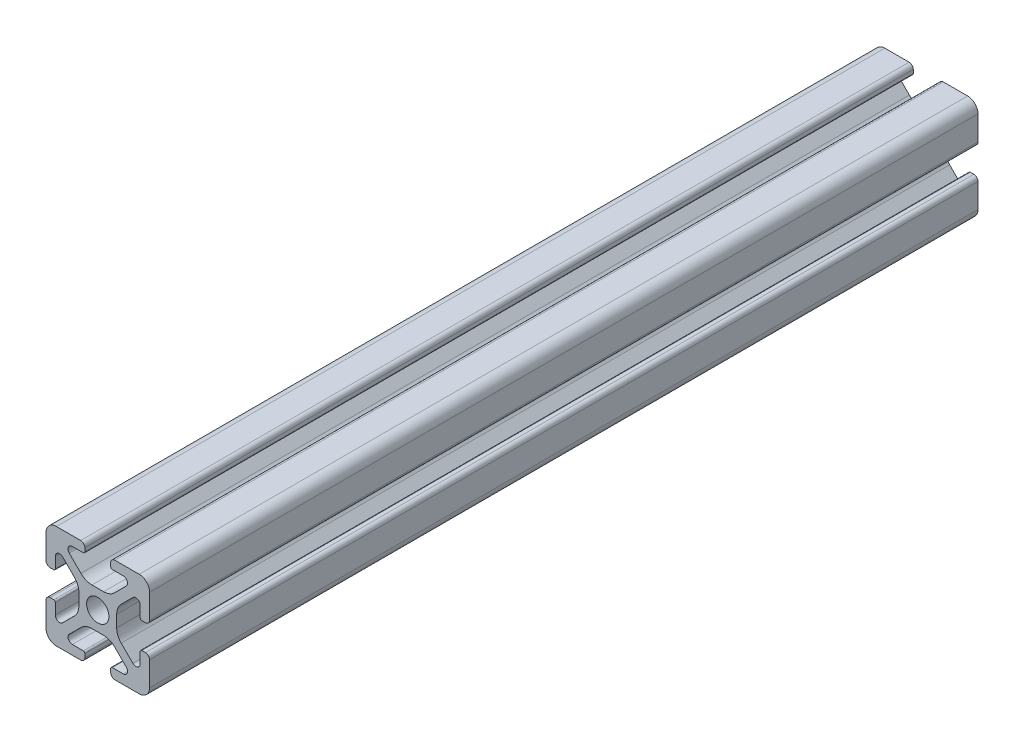
SolidWorks part; units mm, degrees
material "Alliage 1060"
ref_plane "Plan de face" through (0, 0, 0) normal (0, 0, 1) x (1, 0, 0)
ref_plane "Plan de dessus" through (0, 0, 0) normal (0, 1, 0) x (1, 0, 0)
ref_plane "Plan de droite" through (0, 0, 0) normal (1, 0, 0) x (0, 0, -1)
sketch "Esquisse1" plane through (0, 0, 0) normal (0, 0, 1) x (1, 0, 0)
  line L108 (-3.2559, 4.5287) -> (-5.5062, 6.779)
  line L109 (-4.9176, 8.2) -> (-2.8, 8.2)
  line L110 (-2.5, 8.5) -> (-2.5, 9.2)
  line L111 (-3.3, 10) -> (-8, 10)
  line L112 (-10, 8) -> (-10, 3.3)
  line L113 (-9.2, 2.5) -> (-8.5, 2.5)
  line L114 (-8.2, 2.8) -> (-8.2, 4.9176)
  line L115 (-6.779, 5.5062) -> (-4.5287, 3.2559)
  line L116 (-3.65, 1.1346) -> (-3.65, -1.1346)
  line L117 (-4.5287, -3.2559) -> (-6.779, -5.5062)
  line L118 (-8.2, -4.9176) -> (-8.2, -2.8)
  line L119 (-8.5, -2.5) -> (-9.2, -2.5)
  line L120 (-10, -3.3) -> (-10, -8)
  line L121 (-8, -10) -> (-3.3, -10)
  line L122 (-2.5, -9.2) -> (-2.5, -8.5)
  line L123 (-2.8, -8.2) -> (-4.9176, -8.2)
  line L124 (-5.5062, -6.779) -> (-3.2559, -4.5287)
  line L125 (-1.1346, -3.65) -> (1.1346, -3.65)
  line L126 (3.2559, -4.5287) -> (5.5062, -6.779)
  line L127 (4.9176, -8.2) -> (2.8, -8.2)
  line L128 (2.5, -8.5) -> (2.5, -9.2)
  line L129 (3.3, -10) -> (8, -10)
  line L130 (10, -8) -> (10, -3.3)
  line L131 (9.2, -2.5) -> (8.5, -2.5)
  line L132 (8.2, -2.8) -> (8.2, -4.9176)
  line L133 (6.779, -5.5062) -> (4.5287, -3.2559)
  line L134 (3.65, -1.1346) -> (3.65, 1.1346)
  line L135 (4.5287, 3.2559) -> (6.779, 5.5062)
  line L136 (8.2, 4.9176) -> (8.2, 2.8)
  line L137 (8.5, 2.5) -> (9.2, 2.5)
  line L138 (10, 3.3) -> (10, 8)
  line L139 (8, 10) -> (3.3, 10)
  line L140 (2.5, 9.2) -> (2.5, 8.5)
  line L141 (2.8, 8.2) -> (4.9176, 8.2)
  line L142 (5.5062, 6.779) -> (3.2559, 4.5287)
  line L143 (1.1346, 3.65) -> (-1.1346, 3.65)
  arc A42 (-2.15, 0) -> (2.15, 0) centre (0, 0) ccw
  arc A43 (2.15, 0) -> (-2.15, 0) centre (0, 0) ccw
  arc A108 (-4.9176, 8.2) -> (-5.5062, 6.779) centre (-4.9176, 7.3676) ccw
  arc A109 (-2.8, 8.2) -> (-2.5, 8.5) centre (-2.8, 8.5) ccw
  arc A110 (-2.5, 9.2) -> (-3.3, 10) centre (-3.3, 9.2) ccw
  arc A111 (-8, 10) -> (-10, 8) centre (-8, 8) ccw
  arc A112 (-10, 3.3) -> (-9.2, 2.5) centre (-9.2, 3.3) ccw
  arc A113 (-8.5, 2.5) -> (-8.2, 2.8) centre (-8.5, 2.8) ccw
  arc A114 (-6.779, 5.5062) -> (-8.2, 4.9176) centre (-7.3676, 4.9176) ccw
  arc A115 (-3.65, 1.1346) -> (-4.5287, 3.2559) centre (-6.65, 1.1346) ccw
  arc A116 (-4.5287, -3.2559) -> (-3.65, -1.1346) centre (-6.65, -1.1346) ccw
  arc A117 (-8.2, -4.9176) -> (-6.779, -5.5062) centre (-7.3676, -4.9176) ccw
  arc A118 (-8.2, -2.8) -> (-8.5, -2.5) centre (-8.5, -2.8) ccw
  arc A119 (-9.2, -2.5) -> (-10, -3.3) centre (-9.2, -3.3) ccw
  arc A120 (-10, -8) -> (-8, -10) centre (-8, -8) ccw
  arc A121 (-3.3, -10) -> (-2.5, -9.2) centre (-3.3, -9.2) ccw
  arc A122 (-2.5, -8.5) -> (-2.8, -8.2) centre (-2.8, -8.5) ccw
  arc A123 (-5.5062, -6.779) -> (-4.9176, -8.2) centre (-4.9176, -7.3676) ccw
  arc A124 (-1.1346, -3.65) -> (-3.2559, -4.5287) centre (-1.1346, -6.65) ccw
  arc A125 (3.2559, -4.5287) -> (1.1346, -3.65) centre (1.1346, -6.65) ccw
  arc A126 (4.9176, -8.2) -> (5.5062, -6.779) centre (4.9176, -7.3676) ccw
  arc A127 (2.8, -8.2) -> (2.5, -8.5) centre (2.8, -8.5) ccw
  arc A128 (2.5, -9.2) -> (3.3, -10) centre (3.3, -9.2) ccw
  arc A129 (8, -10) -> (10, -8) centre (8, -8) ccw
  arc A130 (10, -3.3) -> (9.2, -2.5) centre (9.2, -3.3) ccw
  arc A131 (8.5, -2.5) -> (8.2, -2.8) centre (8.5, -2.8) ccw
  arc A132 (6.779, -5.5062) -> (8.2, -4.9176) centre (7.3676, -4.9176) ccw
  arc A133 (3.65, -1.1346) -> (4.5287, -3.2559) centre (6.65, -1.1346) ccw
  arc A134 (4.5287, 3.2559) -> (3.65, 1.1346) centre (6.65, 1.1346) ccw
  arc A135 (8.2, 4.9176) -> (6.779, 5.5062) centre (7.3676, 4.9176) ccw
  arc A136 (8.2, 2.8) -> (8.5, 2.5) centre (8.5, 2.8) ccw
  arc A137 (9.2, 2.5) -> (10, 3.3) centre (9.2, 3.3) ccw
  arc A138 (10, 8) -> (8, 10) centre (8, 8) ccw
  arc A139 (3.3, 10) -> (2.5, 9.2) centre (3.3, 9.2) ccw
  arc A140 (2.5, 8.5) -> (2.8, 8.2) centre (2.8, 8.5) ccw
  arc A141 (5.5062, 6.779) -> (4.9176, 8.2) centre (4.9176, 7.3676) ccw
  arc A142 (1.1346, 3.65) -> (3.2559, 4.5287) centre (1.1346, 6.65) ccw
  arc A143 (-3.2559, 4.5287) -> (-1.1346, 3.65) centre (-1.1346, 6.65) ccw
extrude "Boss.-Extru.1" add sketch "Esquisse1" along normal blind 160
